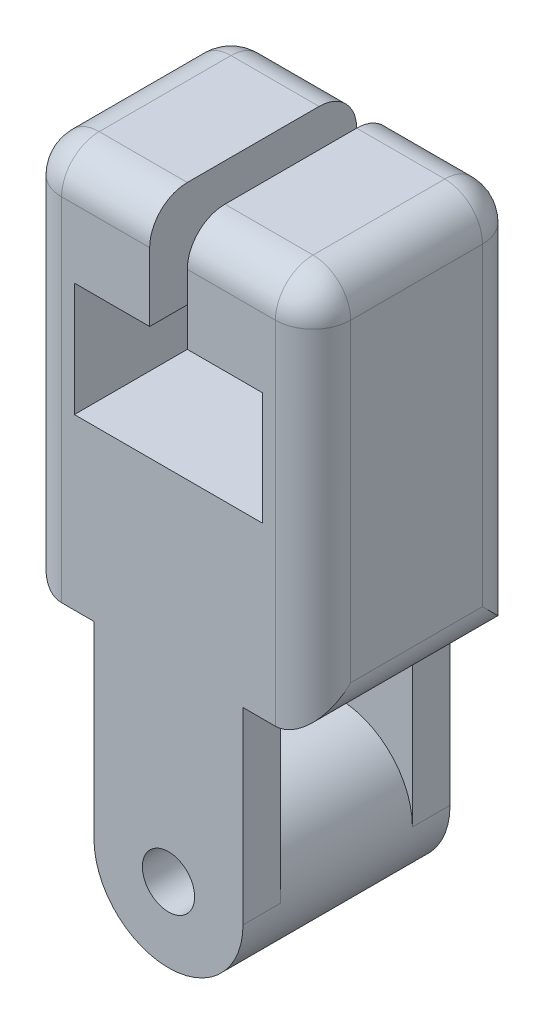
SolidWorks part; units mm, degrees
material "6061-T6 (SS)"
ref_plane "Front Plane" through (0, 0, 0) normal (0, 0, 1) x (1, 0, 0)
ref_plane "Top Plane" through (0, 0, 0) normal (0, 1, 0) x (1, 0, 0)
ref_plane "Right Plane" through (0, 0, 0) normal (1, 0, 0) x (0, 0, -1)
sketch "Sketch1" plane through (0, 0, 0) normal (0, 0, 1) x (1, 0, 0)
  line L0 (0, 0) -> (42.418, 0)
  line L1 (0, 0) -> (0, -131.318)
  line L2 (0, -131.318) -> (97.536, -131.318)
  line L3 (97.536, -131.318) -> (97.536, 0)
  line L4 (97.536, 0) -> (55.118, 0)
  line L5 (55.118, 0) -> (55.118, -36.068)
  line L6 (55.118, -36.068) -> (80.518, -36.068)
  line L7 (80.518, -36.068) -> (80.518, -74.168)
  line L8 (42.418, 0) -> (42.418, -35.7449)
  line L9 (42.418, -35.7449) -> (17.018, -35.7449)
  line L10 (17.018, -35.7449) -> (17.018, -74.168)
  line L11 (17.018, -74.168) -> (80.518, -74.168)
  dimension "D1" = 42.418
  dimension "D2" = 38.1
  dimension "D3" = 63.5
  dimension "D4" = 17.018
  dimension "D5" = 36.068
  dimension "D6" = 57.15
extrude "Boss-Extrude1" add sketch "Sketch1" along normal blind 69.85
sketch "Sketch2" plane through (0, -131.318, 0) normal (0, -1, 0) x (1, 0, 0)
  line L0 (48.768, 69.85) -> (48.768, 0) construction
  line L1 (0, 69.85) -> (97.536, 69.85) construction
  line L2 (23.622, 12.7) -> (73.914, 12.7)
  line L3 (73.914, 12.7) -> (73.914, 0)
  line L4 (0, 34.925) -> (97.536, 34.925) construction
  line L5 (0, 69.85) -> (0, 0) construction
  line L6 (97.536, 69.85) -> (97.536, 0) construction
  line L7 (0, 0) -> (97.536, 0) construction
  line L8 (73.914, 0) -> (23.622, 0)
  line L9 (23.622, 0) -> (23.622, 12.7)
  line L10 (73.914, 69.85) -> (23.622, 69.85)
  line L11 (73.914, 57.15) -> (73.914, 69.85)
  line L12 (23.622, 57.15) -> (73.914, 57.15)
  line L13 (23.622, 69.85) -> (23.622, 57.15)
  point P13 (48.768, 12.7)
  dimension "D1" = 50.292
  dimension "D2" = 12.7
extrude "Boss-Extrude2" add sketch "Sketch2" along normal blind 63.5
sketch "Sketch5" plane through (0, 0, 0) normal (0, 0, -1) x (-1, 0, 0)
  line L0 (-23.622, -194.818) -> (-73.914, -194.818) construction
  circle A0 centre (-48.768, -194.818) radius 25.146
extrude "Boss-Extrude3" add sketch "Sketch5" against normal blind 69.85
sketch "Sketch8" plane through (0, 0, 69.85) normal (0, 0, 1) x (1, 0, 0)
  circle A0 centre (48.768, -194.818) radius 8.8085
extrude "Cut-Extrude2" cut sketch "Sketch8" against normal through all
fillet "Fillet7" radius 12.7 12 edges at (21.209, 0, 0) (21.209, 0, 69.85) (76.327, 0, 0) (76.327, 0, 69.85) (0, 0, 34.925) (0, -65.659, 0) (0, -65.659, 69.85) (0, -131.318, 34.925) (97.536, 0, 34.925) (97.536, -65.659, 0) (97.536, -65.659, 69.85) (97.536, -131.318, 34.925)
